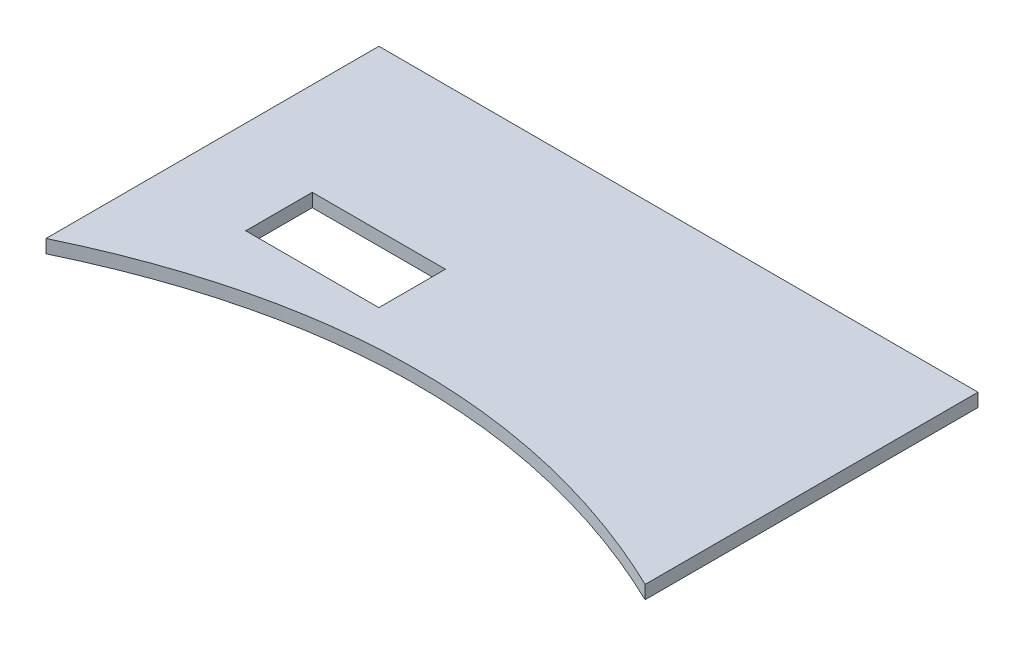
SolidWorks part; units mm, degrees
ref_plane "Front Plane" through (0, 0, 0) normal (0, 0, 1) x (1, 0, 0)
ref_plane "Top Plane" through (0, 0, 0) normal (0, 1, 0) x (1, 0, 0)
ref_plane "Right Plane" through (0, 0, 0) normal (1, 0, 0) x (0, 0, -1)
sketch "Sketch1" plane through (0, 0, 0) normal (0, 1, 0) x (1, 0, 0)
  line L0 (-22.5, -12.5) -> (-22.5, 12.5)
  line L1 (-22.5, 12.5) -> (22.5, 12.5)
  line L2 (22.5, 12.5) -> (22.5, -12.5)
  spline S1 degree 3 poles (-22.5, -12.5) (-22.4398, -12.4711) (-21.7203, -12.1267) (-20.0333, -11.3582) (-16.4872, -9.9296) (-11.6493, -8.4284) (-5.8311, -7.3447) (0, -6.9812) (5.8311, -7.3447) (11.6493, -8.4284) (16.4872, -9.9296) (20.0333, -11.3582) (21.7203, -12.1267) (22.4398, -12.4711) (22.5, -12.5) knots 0.029712 0.029712 0.029712 0.029712 0.033516 0.075187 0.135875 0.25725 0.378625 0.5 0.621375 0.74275 0.864125 0.924813 0.966484 0.970288 0.970288 0.970288 0.970288
  point P0 (22.5, -12.5)
  point P1 (0, 12.5)
  point P2 (-22.5, 0)
  dimension "D2" = 45
  dimension "D3" = 25
extrude "Boss-Extrude1" add sketch "Sketch1" along normal blind 1
sketch "Sketch2" plane through (0, 1, 0) normal (0, 1, 0) x (1, 0, 0)
  line L0 (-22.5, 12.5) -> (-22.5, -12.5) construction
  line L1 (-15.5, -4.5) -> (-5.5, -4.5)
  line L2 (-15.5, -4.5) -> (-15.5, 0.5)
  line L3 (-15.5, 0.5) -> (-5.5, 0.5)
  line L4 (-5.5, -4.5) -> (-5.5, 0.5)
  line L5 (22.5, 12.5) -> (-22.5, 12.5) construction
  dimension "D1" = 7
  dimension "D2" = 17
  dimension "D3" = 5
  dimension "D4" = 10
extrude "Cut-Extrude1" cut sketch "Sketch2" against normal blind 1
